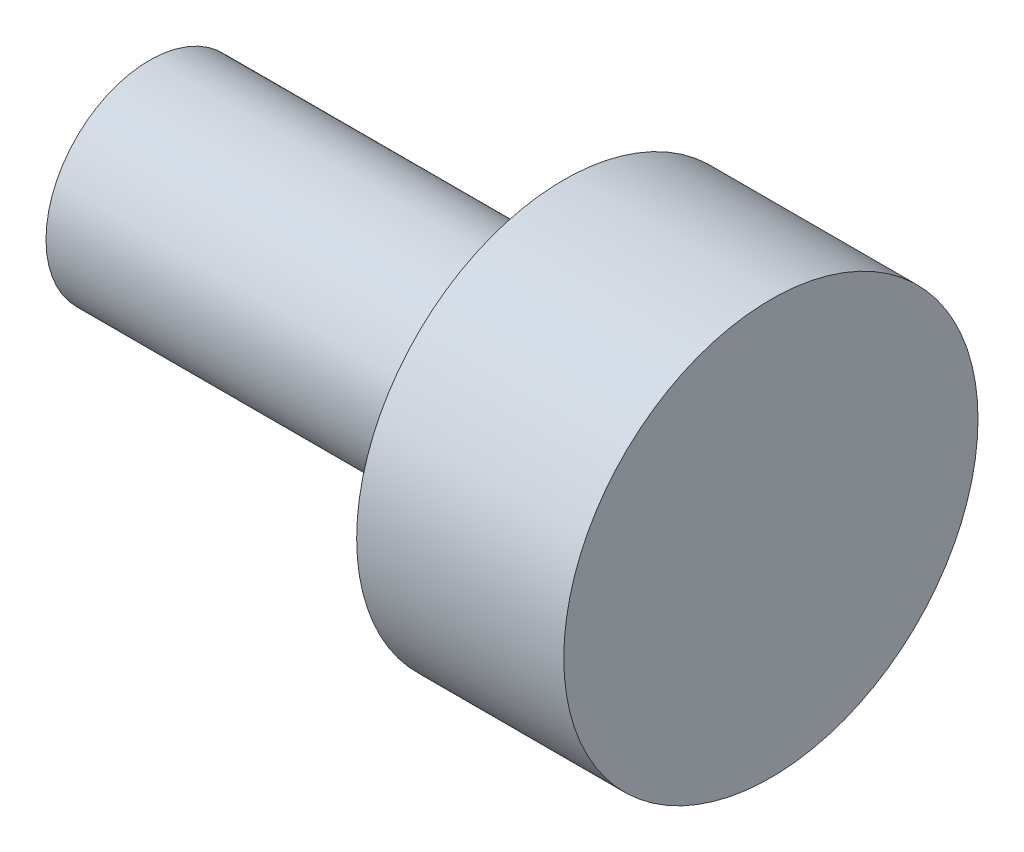
SolidWorks part; units mm, degrees
ref_plane "Front Plane" through (0, 0, 0) normal (0, 0, 1) x (1, 0, 0)
ref_plane "Top Plane" through (0, 0, 0) normal (0, 1, 0) x (1, 0, 0)
ref_plane "Right Plane" through (0, 0, 0) normal (1, 0, 0) x (0, 0, -1)
sketch "Sketch1" plane through (0, 0, 0) normal (0, 0, 1) x (1, 0, 0)
  line L0 (-116.8358, 27.1754) -> (-105.8358, 27.1754)
  line L1 (-105.8358, 27.1754) -> (-105.8358, 28.1754)
  line L2 (-105.8358, 28.1754) -> (-103.8358, 28.1754)
  line L3 (-103.8358, 28.1754) -> (-103.8358, 26.1754)
  line L4 (-116.8358, 27.1754) -> (-116.8358, 26.1754)
  line L5 (-116.8358, 26.1754) -> (-103.8358, 26.1754) construction
  line L6 (-103.8358, 26.1754) -> (-116.8358, 26.1754)
revolve "Revolve1" add sketch "Sketch1" angle 360 about L5
sketch "Sketch2" plane through (-116.8358, 0, 0) normal (-1, 0, 0) x (0, 0, 1)
  line L1 (-1.174, 27.3227) -> (1.2121, 27.3227)
  line L2 (-1.174, 27.3227) -> (-1.174, 25.0738)
  line L3 (-1.174, 25.0738) -> (1.2121, 25.0738)
  line L4 (1.2121, 27.3227) -> (1.2121, 25.0738)
extrude "Cut-Extrude1" cut sketch "Sketch2" against normal blind 3
sketch "Sketch3" plane through (-113.8358, 0, 0) normal (-1, 0, 0) x (0, 0, 1)
  line L1 (-1.2121, 27.4218) -> (1.1435, 27.4218)
  line L2 (-1.2121, 27.4218) -> (-1.2121, 25.0967)
  line L3 (-1.2121, 25.0967) -> (1.1435, 25.0967)
  line L4 (1.1435, 27.4218) -> (1.1435, 25.0967)
extrude "Cut-Extrude2" cut sketch "Sketch3" against normal blind 4
